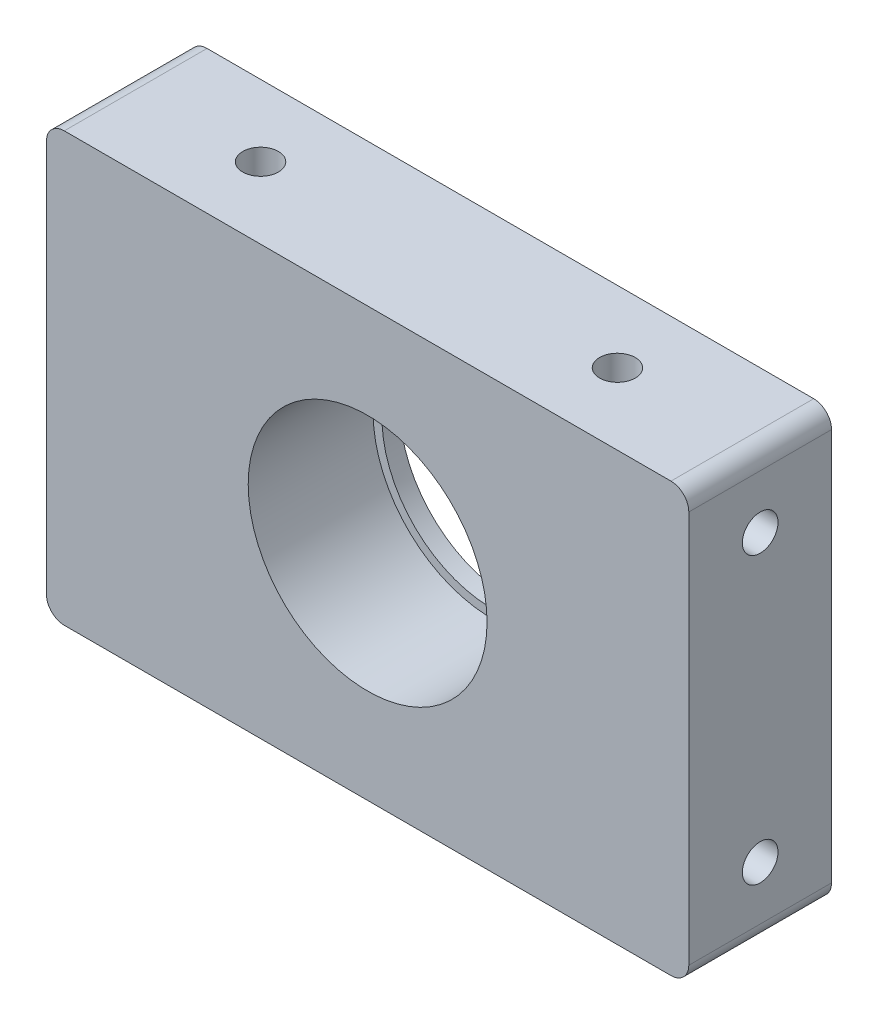
SolidWorks part; units mm, degrees
ref_plane "Front Plane" through (0, 0, 0) normal (0, 0, 1) x (1, 0, 0)
ref_plane "Top Plane" through (0, 0, 0) normal (0, 1, 0) x (1, 0, 0)
ref_plane "Right Plane" through (0, 0, 0) normal (1, 0, 0) x (0, 0, -1)
sketch "Sketch1" plane through (0, 0, 0) normal (0, 0, 1) x (1, 0, 0)
  line L0 (-239.6796, 0) -> (239.6796, 0) construction
  line L1 (0, -172.6883) -> (0, 172.6883) construction
  line L3 (-107.95, -76.2) -> (107.95, -76.2)
  line L4 (-114.3, -69.85) -> (-114.3, 69.85)
  line L5 (-107.95, 76.2) -> (107.95, 76.2)
  line L6 (114.3, -69.85) -> (114.3, 69.85)
  line L7 (-114.3, -76.2) -> (114.3, 76.2) construction
  line L8 (-114.3, 76.2) -> (114.3, -76.2) construction
  arc A0 (107.95, 76.2) -> (114.3, 69.85) centre (107.95, 69.85) cw
  arc A1 (107.95, -76.2) -> (114.3, -69.85) centre (107.95, -69.85) ccw
  arc A2 (-107.95, -76.2) -> (-114.3, -69.85) centre (-107.95, -69.85) cw
  arc A3 (-114.3, 69.85) -> (-107.95, 76.2) centre (-107.95, 69.85) cw
  point P0 (0, 0)
  point P4 (0, 0)
  point P8 (0, 0)
  dimension "D3" = 6.35
  dimension "D1" = 228.6
  dimension "D2" = 152.4
extrude "Boss-Extrude1" add sketch "Sketch1" along normal mid plane 50.8
sketch "Sketch2" plane through (0, 0, 25.4) normal (0, 0, 1) x (1, 0, 0)
  circle A0 centre (0, 0) radius 42.5005
  dimension "D1" = 85.0011
extrude "Cut-Extrude1" cut sketch "Sketch2" against normal blind 44.45
sketch "Sketch3" plane through (0, 0, -19.05) normal (0, 0, 1) x (1, 0, 0)
  circle A0 centre (0, 0) radius 39.37
  dimension "D1" = 78.74
extrude "Cut-Extrude2" cut sketch "Sketch3" against normal blind 31.75
sketch "Sketch4" plane through (0, 76.2, 0) normal (0, 1, 0) x (1, 0, 0)
  line L0 (-143.8538, 0) -> (143.8538, 0) construction
  line L1 (0, -62.6914) -> (0, 62.6914) construction
  circle A0 centre (-63.5, 0) radius 6.35
  circle A1 centre (63.5, 0) radius 6.35
  point P4 (0, 0)
  point P8 (0, 0)
  dimension "D1" = 12.7
  dimension "D2" = 63.5
extrude "Cut-Extrude3" cut sketch "Sketch4" against normal blind 19.05
sketch "Sketch5" plane through (0, -76.2, 0) normal (0, -1, 0) x (1, 0, 0)
  line L0 (-160.2509, 0) -> (160.2509, 0) construction
  line L1 (0, -54.1692) -> (0, 54.1692) construction
  circle A0 centre (-63.5, 0) radius 6.35
  circle A1 centre (63.5, 0) radius 6.35
  point P4 (0, 0)
  point P8 (0, 0)
  dimension "D1" = 12.7
  dimension "D2" = 63.5
extrude "Cut-Extrude4" cut sketch "Sketch5" against normal blind 19.05
sketch "Sketch6" plane through (114.3, 0, 0) normal (1, 0, 0) x (0, 0, -1)
  line L0 (-64.213, 0) -> (64.213, 0) construction
  line L1 (0, -110.551) -> (0, 110.551) construction
  circle A0 centre (0, 50.8) radius 6.35
  circle A1 centre (0, -50.8) radius 6.35
  point P4 (0, 0)
  point P8 (0, 0)
  dimension "D1" = 12.7
  dimension "D2" = 50.8
extrude "Cut-Extrude5" cut sketch "Sketch6" against normal blind 19.05
sketch "Sketch7" plane through (-114.3, 0, 0) normal (-1, 0, 0) x (0, 0, 1)
  line L0 (-70.9572, 0) -> (70.9572, 0) construction
  line L1 (0, -113.5185) -> (0, 113.5185) construction
  circle A0 centre (0, 50.8) radius 6.35
  circle A1 centre (0, -50.8) radius 6.35
  point P4 (0, 0)
  point P8 (0, 0)
  dimension "D1" = 12.7
  dimension "D2" = 50.8
extrude "Cut-Extrude6" cut sketch "Sketch7" against normal blind 19.05
